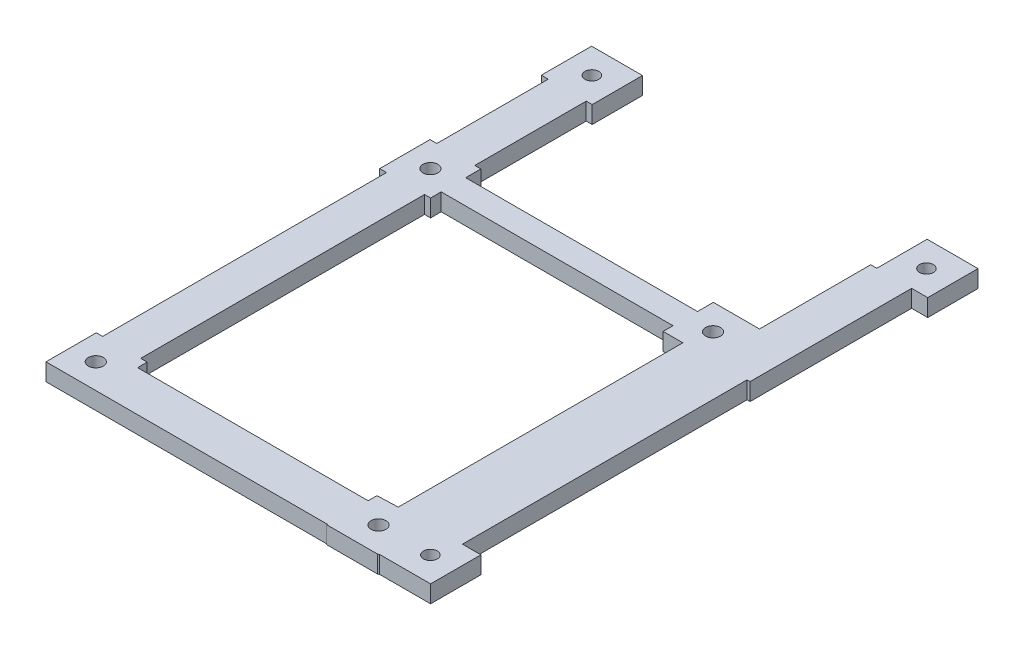
SolidWorks part; units mm, degrees
ref_plane "Front Plane" through (0, 0, 0) normal (0, 0, 1) x (1, 0, 0)
ref_plane "Top Plane" through (0, 0, 0) normal (0, 1, 0) x (1, 0, 0)
ref_plane "Right Plane" through (0, 0, 0) normal (1, 0, 0) x (0, 0, -1)
sketch "Sketch1" plane through (0, 0, 0) normal (0, 1, 0) x (1, 0, 0)
  line L0 (9.7627, 65.6695) -> (10.9425, 65.6695)
  line L1 (9.7467, 93.7035) -> (18.5632, 93.7035)
  line L2 (9.7467, 93.7035) -> (9.7467, 84.984)
  line L3 (9.7467, 84.984) -> (10.9425, 84.984)
  line L4 (18.5632, 93.7035) -> (18.5632, 84.984)
  line L5 (13.3018, 90.1876) -> (15.0082, 88.4999) construction
  line L6 (13.3018, 88.4999) -> (15.0082, 90.1876) construction
  line L7 (9.7627, 65.6695) -> (9.7627, 56.9501)
  line L8 (9.7627, 56.9501) -> (10.9425, 56.9501)
  line L9 (18.5792, 65.6695) -> (18.5792, 63.04)
  line L12 (67.814, 93.8036) -> (76.6305, 93.8036)
  line L13 (67.814, 93.8036) -> (67.814, 85.0841)
  line L14 (73.8433, 85.0841) -> (76.6305, 85.0841)
  line L15 (76.6305, 93.8036) -> (76.6305, 85.0841)
  line L16 (71.3893, 90.2677) -> (73.0873, 88.5883) construction
  line L17 (71.2851, 88.5171) -> (72.9912, 90.2044) construction
  line L22 (73.3172, 7.7395) -> (76.5163, 7.7395)
  line L24 (9.8418, 7.742) -> (10.9425, 7.742)
  line L25 (9.8418, 7.742) -> (9.8418, -0.9774)
  line L26 (9.8418, -0.9774) -> (18.6583, -0.9774)
  line L27 (18.6583, 7.742) -> (18.6583, 6.0828)
  line L28 (13.2994, 4.3225) -> (15.1431, 2.499) construction
  line L29 (13.2588, 2.402) -> (15.1066, 4.2294) construction
  line L31 (58.6262, 7.6139) -> (58.6262, 6.0828)
  line L32 (58.6262, -1.1056) -> (67.4427, -1.1056)
  line L34 (62.1323, 4.1463) -> (63.9688, 2.33) construction
  line L35 (62.216, 2.4447) -> (64.0643, 4.2728) construction
  line L36 (67.6998, -0.98) -> (76.5163, -0.98)
  line L37 (76.5163, 7.7395) -> (76.5163, -0.98)
  line L38 (71.2966, 4.1823) -> (73.003, 2.4947) construction
  line L39 (71.2616, 2.5426) -> (72.966, 4.2282) construction
  line L40 (58.7656, 65.7963) -> (66.7555, 65.7963)
  line L41 (58.7656, 65.7963) -> (58.7656, 63.04)
  line L42 (58.7656, 57.0769) -> (62.1893, 57.0769)
  line L44 (62.2881, 62.3126) -> (64.1333, 60.4877) construction
  line L45 (62.1943, 60.4679) -> (64.0414, 62.2946) construction
  line L46 (17.5314, 84.984) -> (18.5632, 84.984)
  line L48 (10.9425, 84.984) -> (10.9425, 65.6695)
  line L50 (17.5314, 84.984) -> (17.5314, 65.6695)
  line L51 (18.5792, 63.04) -> (58.7656, 63.04)
  line L53 (18.5792, 58.7938) -> (58.7656, 58.7938)
  line L56 (62.1893, 57.0769) -> (62.1893, 7.7395)
  line L58 (73.3172, 57.0769) -> (73.3172, 7.7395)
  line L63 (58.6262, 6.0828) -> (18.6583, 6.0828)
  line L65 (58.6262, -0.9774) -> (18.6583, -0.9774)
  line L69 (66.7555, 85.0841) -> (67.814, 85.0841)
  line L70 (73.8433, 57.0769) -> (73.8433, 85.0841)
  line L71 (17.5314, 65.6695) -> (18.5792, 65.6695)
  line L73 (17.5314, 56.9501) -> (17.5314, 7.742)
  line L74 (18.5792, 58.7938) -> (18.5792, 56.9501)
  line L76 (17.5314, 56.9501) -> (18.5792, 56.9501)
  line L77 (13.255, 60.404) -> (15.103, 62.2316) construction
  line L78 (13.2224, 62.2479) -> (15.0709, 60.4197) construction
  line L79 (58.7656, 58.7938) -> (58.7656, 57.0769)
  line L80 (58.6262, -0.9774) -> (58.6262, -1.1056)
  line L81 (66.7555, 65.7963) -> (66.7555, 85.0841)
  line L82 (58.6262, 7.6139) -> (62.1893, 7.7395)
  line L84 (73.3172, 57.0769) -> (73.8433, 57.0769)
  line L85 (67.4427, -1.1056) -> (67.6998, -0.98)
  line L86 (17.5314, 7.742) -> (18.6583, 7.742)
  line L87 (10.9425, 56.9501) -> (10.9425, 7.742)
  circle A0 centre (14.155, 3.3437) radius 1.3
  circle A1 centre (63.155, 3.3437) radius 1.3
  circle A2 centre (14.155, 61.3421) radius 1.3
  circle A3 centre (63.155, 61.3437) radius 1.3
  circle A4 centre (72.155, 3.3437) radius 1.2
  circle A5 centre (72.155, 89.3437) radius 1.2
  circle A6 centre (14.155, 89.3437) radius 1.2
  dimension "D1" = 58
  dimension "D3" = 58
  dimension "D5" = 58
  dimension "D2" = 49
  dimension "D4" = 86
  dimension "D6" = 49
  dimension "D7" = 86
extrude "Boss-Extrude1" add sketch "Sketch1" along normal blind 3
